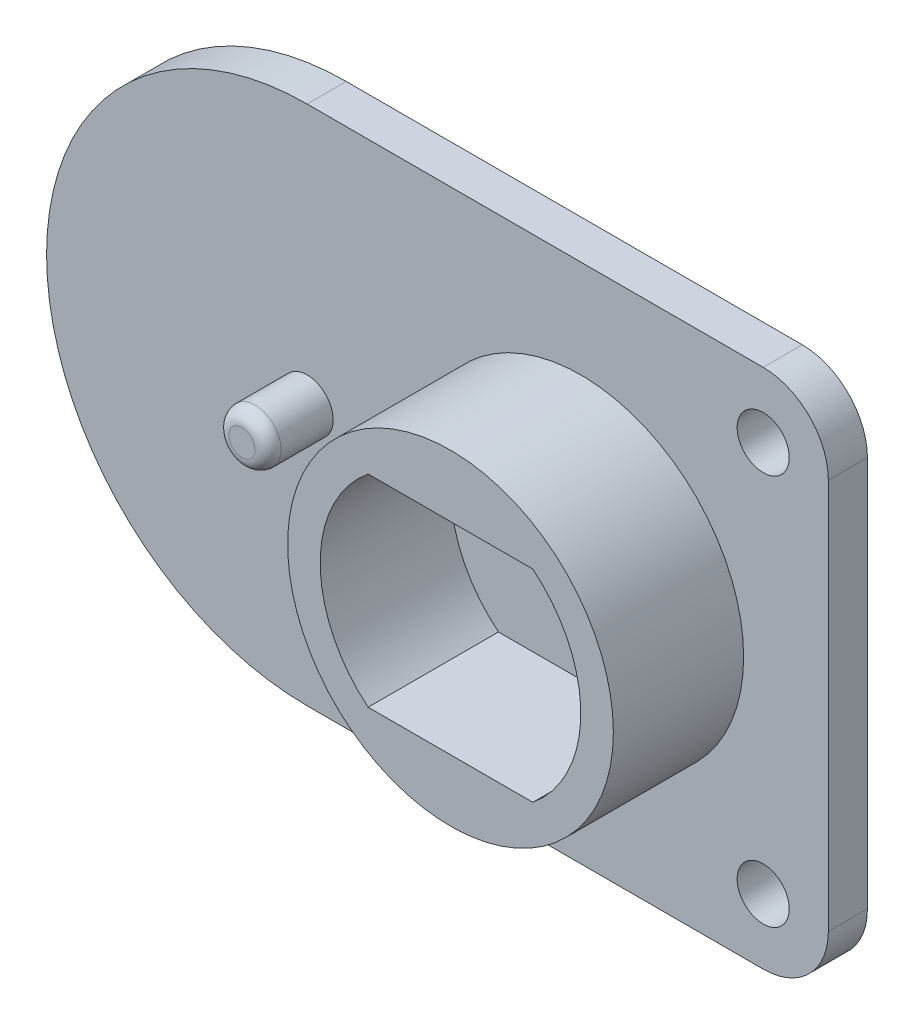
SolidWorks part; units mm, degrees
ref_plane "Ebene vorne" through (0, 0, 0) normal (0, 0, 1) x (1, 0, 0)
ref_plane "Ebene oben" through (0, 0, 0) normal (0, 1, 0) x (1, 0, 0)
ref_plane "Ebene rechts" through (0, 0, 0) normal (1, 0, 0) x (0, 0, -1)
sketch "Skizze1" plane through (0, 0, 0) normal (0, 0, 1) x (1, 0, 0)
  line L0 (0, 20) -> (40, 20)
  line L1 (0, -20) -> (40, -20)
  line L2 (40, 20) -> (40, -20)
  line L3 (0, 0) -> (40, 0) construction
  circle A0 centre (0, 0) radius 20
  circle A1 centre (0, 0) radius 1
  circle A2 centre (21, 0) radius 3.5
  circle A3 centre (35, -15) radius 2
  circle A4 centre (35, 15) radius 2
  dimension "D1" = 40
  dimension "D2" = 2
  dimension "D4" = 7
  dimension "D8" = 4
  dimension "D3" = 40
  dimension "D5" = 21
  dimension "D6" = 5
  dimension "D7" = 5
extrude "Aufsatz-Linear austragen1" add sketch "Skizze1" along normal blind 3
fillet "Verrundung1" radius 5 2 edges at (40, -20, 1.5) (40, 20, 1.5)
sketch "Skizze2" plane through (0, 0, 3) normal (0, 0, 1) x (1, 0, 0)
  line L0 (14.6804, 7.75) -> (27.3196, 7.75)
  line L1 (27.3196, -7.75) -> (14.6804, -7.75)
  line L2 (21, -7.75) -> (21, 7.75)
  circle A0 centre (21, 0) radius 12.5
  circle A1 centre (21, 0) radius 10
  circle A2 centre (21, 0) radius 1.5 construction
  point P10 (0, 0)
  dimension "D2" = 20
  dimension "D3" = 25
  dimension "D4" = 3
  dimension "D1" = 15.5
extrude "Aufsatz-Linear austragen2" add sketch "Skizze2" along normal blind 10 contours A0 A1 | L1 A1 | L0 A1
sketch "Skizze3" plane through (0, 0, 3) normal (0, 0, 1) x (1, 0, 0)
  circle A0 centre (0, 0) radius 2
  dimension "D1" = 4
extrude "Aufsatz-Linear austragen3" add sketch "Skizze3" along normal blind 5
fillet "Verrundung2" radius 1 1 edges at (2, 0, 8)
